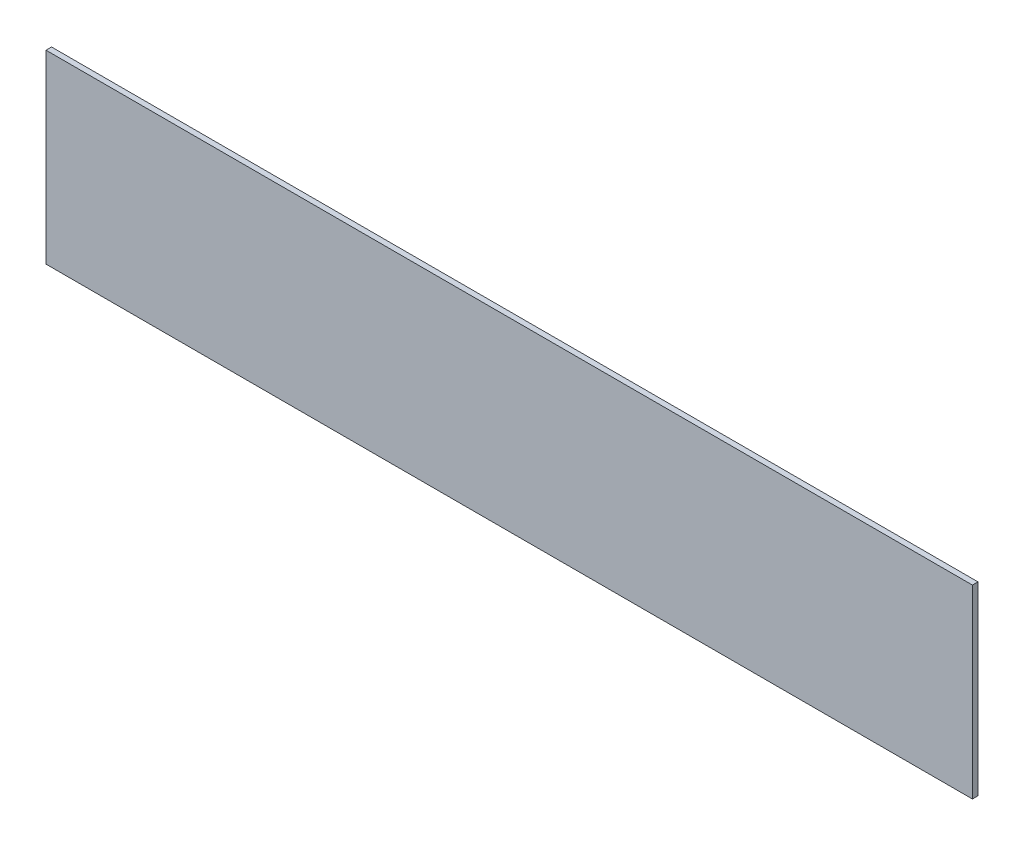
SolidWorks part; units mm, degrees
ref_plane "Спереди" through (0, 0, 0) normal (0, 0, 1) x (1, 0, 0)
ref_plane "Сверху" through (0, 0, 0) normal (0, 1, 0) x (1, 0, 0)
ref_plane "Справа" through (0, 0, 0) normal (1, 0, 0) x (0, 0, -1)
sketch "Эскиз1" plane through (0, 0, 0) normal (0, 0, 1) x (1, 0, 0)
  line L1 (0, 20) -> (100, 20)
  line L2 (0, 20) -> (0, 0)
  line L3 (0, 0) -> (100, 0)
  line L4 (100, 20) -> (100, 0)
  dimension "D1" = 100
  dimension "D2" = 20
extrude "100/20/0,6" add sketch "Эскиз1" along normal blind 0.6
